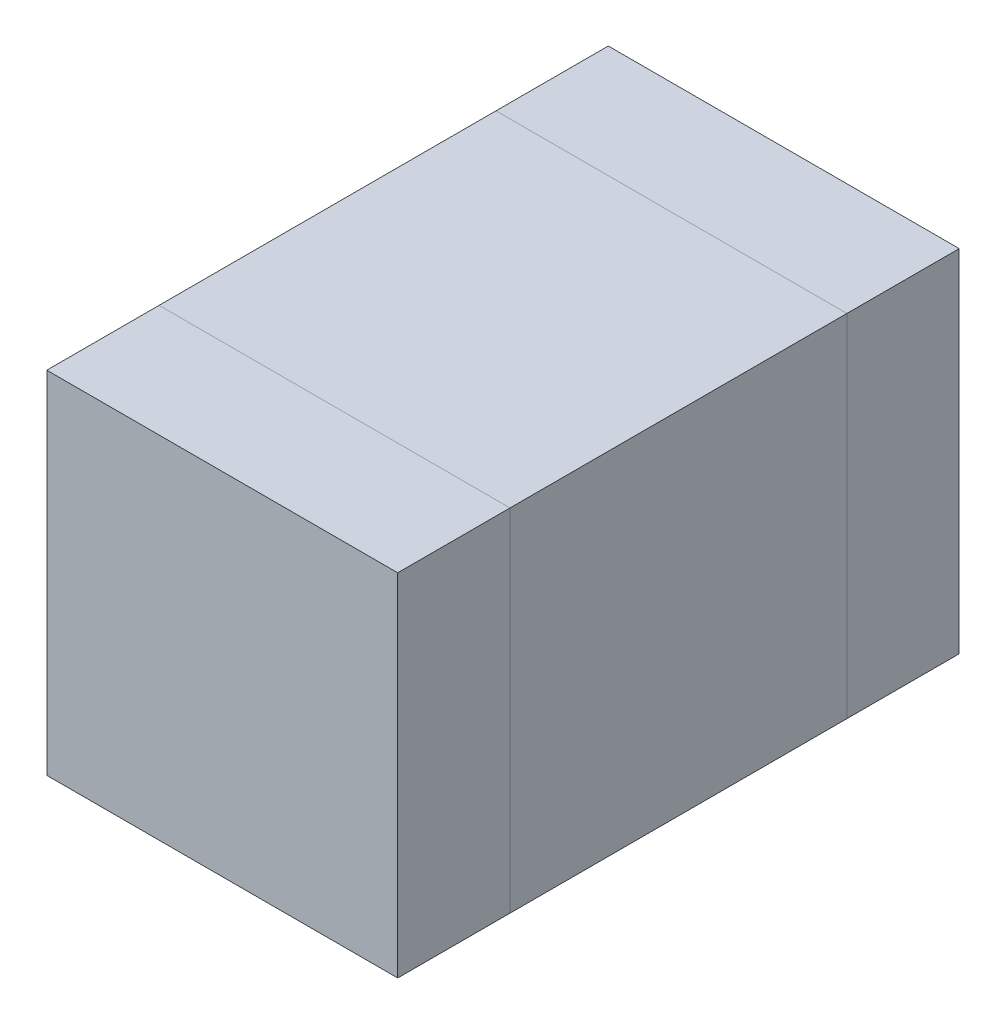
SolidWorks part; units mm, degrees
ref_plane "Front Plane" through (0, 0, 0) normal (0, 0, 1) x (1, 0, 0)
ref_plane "Top Plane" through (0, 0, 0) normal (0, 1, 0) x (1, 0, 0)
ref_plane "Right Plane" through (0, 0, 0) normal (1, 0, 0) x (0, 0, -1)
sketch "MainBodyS" plane through (0, 0, 0) normal (0, 1, 0) x (1, 0, 0)
  line L1 (-0.625, 0.6) -> (0.625, 0.6)
  line L2 (-0.625, 0.6) -> (-0.625, -0.6)
  line L3 (-0.625, -0.6) -> (0.625, -0.6)
  line L4 (0.625, 0.6) -> (0.625, -0.6)
  line L5 (-0.625, 0.6) -> (0.625, -0.6) construction
  line L6 (-0.625, -0.6) -> (0.625, 0.6) construction
  point P0 (0, 0)
  dimension "Length" = 1.2
  dimension "Width" = 1.25
extrude "MainBody" add sketch "MainBodyS" along normal blind 1.25
sketch "LeftBodyS" plane through (0, 0, 0) normal (0, -1, 0) x (-1, 0, 0)
  line L1 (0.625, -0.6) -> (-0.625, -0.6)
  line L2 (0.625, -0.6) -> (0.625, -1)
  line L3 (0.625, -1) -> (-0.625, -1)
  line L4 (-0.625, -0.6) -> (-0.625, -1)
  dimension "SolderLength" = 0.4
extrude "LeftBody" add sketch "LeftBodyS" against normal up to surface (1.25 mm away) separate body up to face at (0, 1.25, 0)
sketch "RightBodyS" plane through (0, 0, 0) normal (0, -1, 0) x (1, 0, 0)
  line L0 (0.625, 0.6) -> (0.625, 1) construction
  line L1 (-0.625, -0.6) -> (0.625, -0.6)
  line L2 (-0.625, -0.6) -> (-0.625, -1)
  line L3 (-0.625, -1) -> (0.625, -1)
  line L4 (0.625, -0.6) -> (0.625, -1)
extrude "RightBody" add sketch "RightBodyS" against normal up to surface (1.25 mm away) separate body up to face at (0, 1.25, 0)
